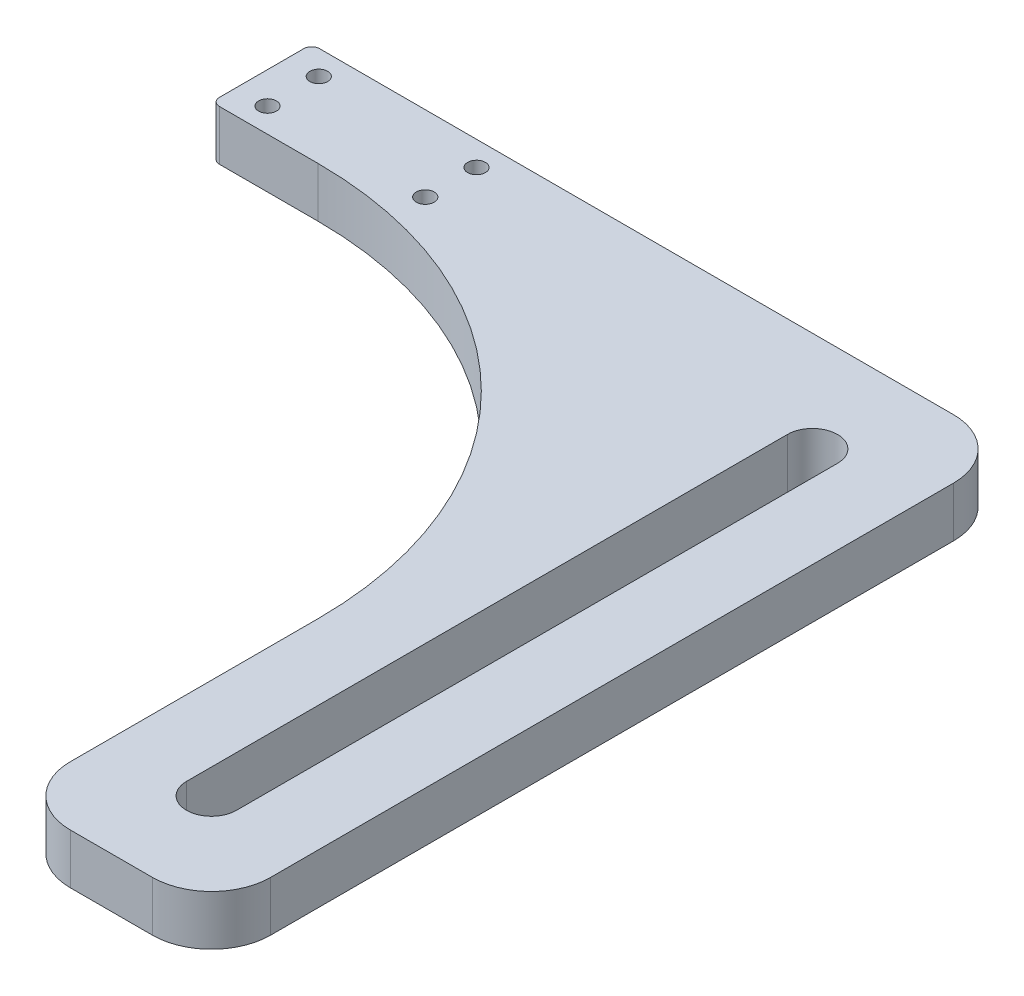
SolidWorks part; units mm, degrees
ref_plane "Front Plane" through (0, 0, 0) normal (0, 0, 1) x (1, 0, 0)
ref_plane "Top Plane" through (0, 0, 0) normal (0, 1, 0) x (1, 0, 0)
ref_plane "Right Plane" through (0, 0, 0) normal (1, 0, 0) x (0, 0, -1)
sketch "Sketch1" plane through (0, 0, 0) normal (0, 1, 0) x (1, 0, 0)
  line L0 (-12.7, 50.8) -> (-76.2, 50.8)
  line L1 (-12.7, -50.8) -> (12.7, -50.8)
  line L2 (-12.7, -50.8) -> (-12.7, 50.8) construction
  line L3 (-12.7, 50.8) -> (12.7, 50.8)
  line L4 (12.7, -50.8) -> (12.7, 50.8)
  line L5 (-12.7, -50.8) -> (12.7, 50.8) construction
  line L6 (-12.7, 50.8) -> (12.7, -50.8) construction
  line L7 (-76.2, 50.8) -> (-76.2, 38.1)
  line L8 (-76.2, 38.1) -> (-62.7, 38.1)
  line L9 (-12.7, -11.9) -> (-12.7, -50.8)
  line L10 (0, -38.1) -> (0, 38.1) construction
  line L13 (-3.175, -38.1) -> (-3.175, 38.1)
  line L14 (3.175, -38.1) -> (3.175, 38.1)
  line L15 (-72.2, 50.8) -> (-72.2, 38.1) construction
  line L16 (-52.2, 50.8) -> (-52.2, 38.1) construction
  line L17 (-72.2, 47.7) -> (-72.2, 50.8) construction
  line L18 (-72.2, 41.2) -> (-72.2, 38.1) construction
  line L19 (-72.2, 47.7) -> (-52.2, 47.7) construction
  line L20 (-72.2, 41.2) -> (-52.2, 41.2) construction
  arc A2 (-62.7, 38.1) -> (-12.7, -11.9) centre (-62.7, -11.9) cw
  arc A3 (-3.175, -38.1) -> (3.175, -38.1) centre (0, -38.1) ccw
  arc A4 (3.175, 38.1) -> (-3.175, 38.1) centre (0, 38.1) ccw
  circle A5 centre (-72.2, 47.7) radius 1.1303
  circle A6 centre (-72.2, 41.2) radius 1.1303
  circle A7 centre (-52.2, 47.7) radius 1.1303
  circle A8 centre (-52.2, 41.2) radius 1.1303
  point P0 (0, 0)
  point P11 (0, 0)
  point P18 (-12.7, 38.1)
  dimension "D7" = 50
  dimension "D11" = 2.2606
  dimension "D1" = 25.4
  dimension "D2" = 101.6
  dimension "D3" = 76.2
  dimension "D4" = 12.7
  dimension "D5" = 6.35
  dimension "D6" = 12.7
  dimension "D8" = 76.2
  dimension "D9" = 4
  dimension "D10" = 20
  dimension "D12" = 6.5
extrude "Boss-Extrude2" add sketch "Sketch1" along normal blind 6.35
fillet "Fillet1" radius 1 2 edges at (-76.2, 3.175, -50.8) (-76.2, 3.175, -38.1)
fillet "Fillet2" radius 7.5 3 edges at (12.7, 3.175, -50.8) (12.7, 3.175, 50.8) (-12.7, 3.175, 50.8)
